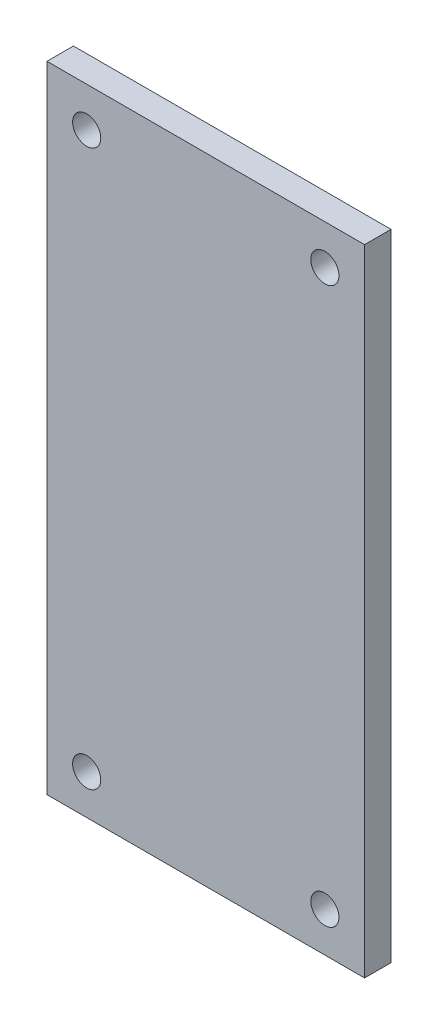
SolidWorks part; units mm, degrees
ref_plane "Front" through (0, 0, 0) normal (0, 0, 1) x (1, 0, 0)
ref_plane "Top" through (0, 0, 0) normal (0, 1, 0) x (1, 0, 0)
ref_plane "Right" through (0, 0, 0) normal (1, 0, 0) x (0, 0, -1)
sketch "Sketch1" plane through (0, 0, 0) normal (0, 0, 1) x (1, 0, 0)
  line L1 (-38.1, -76.2) -> (38.1, -76.2)
  line L2 (-38.1, -76.2) -> (-38.1, 76.2)
  line L3 (-38.1, 76.2) -> (38.1, 76.2)
  line L4 (38.1, -76.2) -> (38.1, 76.2)
  line L5 (-38.1, -76.2) -> (38.1, 76.2) construction
  line L6 (-38.1, 76.2) -> (38.1, -76.2) construction
  point P0 (0, 0)
  dimension "D1" = 76.2
  dimension "D2" = 152.4
extrude "Boss-Extrude1" add sketch "Sketch1" along normal blind 6.35
sketch "Sketch2" plane through (0, 0, 6.35) normal (0, 0, 1) x (1, 0, 0)
  line L0 (-38.1, 66.675) -> (-28.575, 66.675) construction
  line L1 (-38.1, 76.2) -> (-38.1, -76.2) construction
  line L2 (-28.575, 66.675) -> (28.575, 66.675) construction
  line L3 (28.575, 66.675) -> (38.1, 66.675) construction
  line L4 (38.1, -76.2) -> (38.1, 76.2) construction
  line L5 (38.1, 76.2) -> (-38.1, 76.2) construction
  dimension "D1" = 57.15
  dimension "D2" = 9.525
hole_wizard "1/4 Clearance Hole1" positions "Sketch4" profile "Sketch3" hole size "1/4" standard "ANSI Inch" end condition through all
sketch "Sketch4" plane through (0, 0, 6.35) normal (0, 0, 1) x (1, 0, 0)
  point P0 (-28.575, 66.675)
  point P3 (28.575, 66.675)
sketch "Sketch3" plane through (-28.575, 66.675, 6.35) normal (1, 0, 0) x (0, -1, 0)
  line L0 (0, 0) -> (0, 6.35)
  line L1 (0, 6.35) -> (3.3782, 6.35)
  line L2 (3.3782, 6.35) -> (3.3782, 0)
  line L5 (3.3782, 0) -> (0, 0)
  line L11 (0, -6.35) -> (0, 107.95) construction
  dimension "Thru Hole Dia." = 6.7564
  dimension "Thru Hole Depth" = 6.35
mirror "Mirror1" about plane through (0, 0, 0) normal (0, 1, 0) of "1/4 Clearance Hole1"
